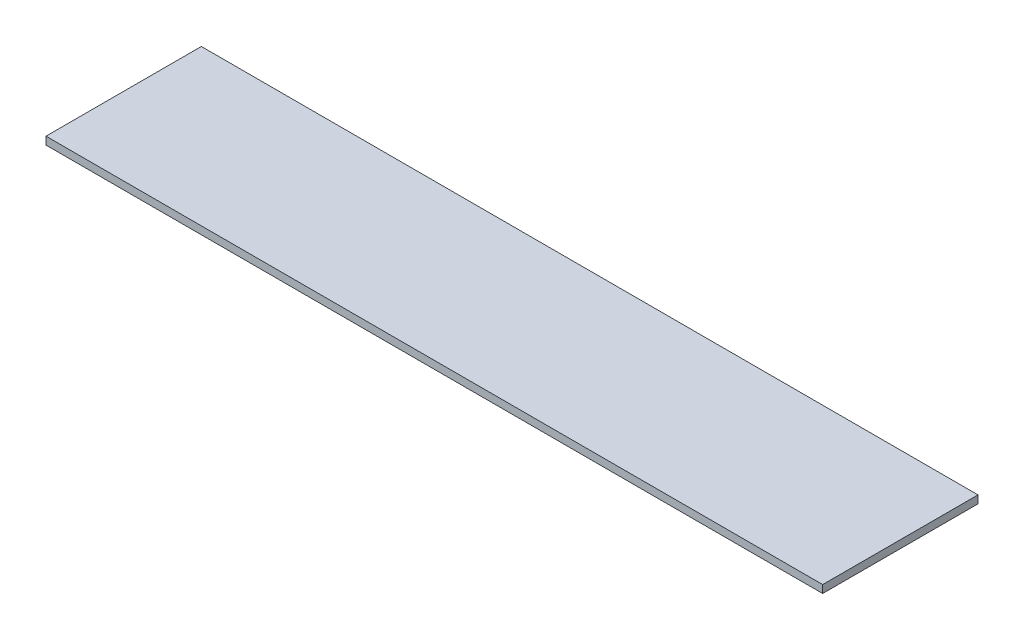
SolidWorks part; units mm, degrees
ref_plane "Front Plane" through (0, 0, 0) normal (0, 0, 1) x (1, 0, 0)
ref_plane "Top Plane" through (0, 0, 0) normal (0, 1, 0) x (1, 0, 0)
ref_plane "Right Plane" through (0, 0, 0) normal (1, 0, 0) x (0, 0, -1)
sketch "Sketch1" plane through (0, 0, 0) normal (0, 1, 0) x (1, 0, 0)
  line L1 (-100, -20) -> (100, -20)
  line L2 (-100, -20) -> (-100, 20)
  line L3 (-100, 20) -> (100, 20)
  line L4 (100, -20) -> (100, 20)
  line L5 (-100, -20) -> (100, 20) construction
  line L6 (-100, 20) -> (100, -20) construction
  point P0 (0, 0)
  dimension "D1" = 200
  dimension "D2" = 40
extrude "Boss-Extrude1" add sketch "Sketch1" along normal blind 2
